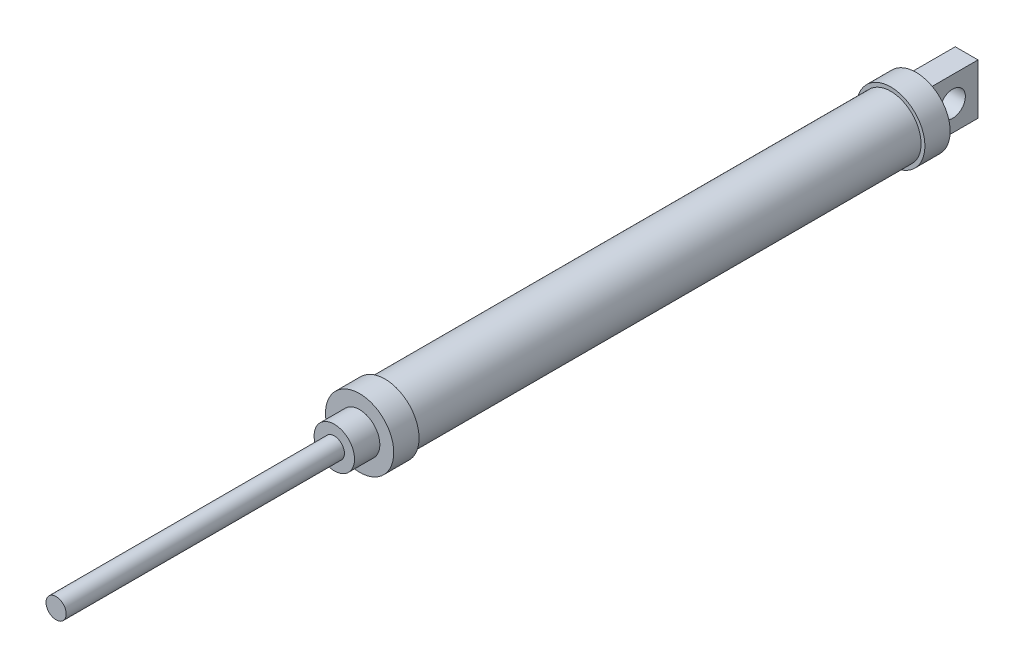
SolidWorks part; units mm, degrees
ref_plane "Front Plane" through (0, 0, 0) normal (0, 0, 1) x (1, 0, 0)
ref_plane "Top Plane" through (0, 0, 0) normal (0, 1, 0) x (1, 0, 0)
ref_plane "Right Plane" through (0, 0, 0) normal (1, 0, 0) x (0, 0, -1)
sketch "Sketch1" plane through (0, 0, 0) normal (0, 0, 1) x (1, 0, 0)
  circle A0 centre (0, 0) radius 13.5
  dimension "D1" = 27
extrude "Boss-Extrude1" add sketch "Sketch1" along normal blind 10
sketch "Sketch2" plane through (0, 0, 10) normal (0, 0, 1) x (1, 0, 0)
  circle A0 centre (0, 0) radius 8
  dimension "D1" = 16
extrude "Boss-Extrude2" add sketch "Sketch2" along normal blind 10
sketch "Sketch3" plane through (0, 0, 0) normal (0, 0, -1) x (-1, 0, 0)
  circle A0 centre (0, 0) radius 12
  dimension "D1" = 24
extrude "Boss-Extrude3" add sketch "Sketch3" along normal blind 200
sketch "Sketch4" plane through (0, 0, -200) normal (0, 0, -1) x (-1, 0, 0)
  circle A0 centre (0, 0) radius 13.5
  dimension "D1" = 27
extrude "Boss-Extrude4" add sketch "Sketch4" along normal blind 10 contours A0
sketch "Sketch5" plane through (0, 0, -210) normal (0, 0, -1) x (-1, 0, 0)
  line L1 (4.5, -10) -> (-4.5, -10)
  line L2 (4.5, -10) -> (4.5, 10)
  line L3 (4.5, 10) -> (-4.5, 10)
  line L4 (-4.5, -10) -> (-4.5, 10)
  line L5 (4.5, -10) -> (-4.5, 10) construction
  line L6 (4.5, 10) -> (-4.5, -10) construction
  point P0 (0, 0)
  dimension "D1" = 9
  dimension "D2" = 20
extrude "Boss-Extrude5" add sketch "Sketch5" along normal blind 20
sketch "Sketch6" plane through (4.5, 0, 0) normal (1, 0, 0) x (0, 0, -1)
  line L0 (210, 10) -> (230, -10) construction
  line L1 (230, -10) -> (210, -10) construction
  line L2 (230, -10) -> (230, 10) construction
  line L3 (230, 10) -> (210, -10) construction
  circle A0 centre (220, 0) radius 5
  dimension "D1" = 10
extrude "Cut-Extrude1" cut sketch "Sketch6" against normal blind 20 contours A0
sketch "Sketch8" plane through (0, 0, 20) normal (0, 0, 1) x (1, 0, 0)
  circle A0 centre (0, 0) radius 4
  dimension "D1" = 8
extrude "Boss-Extrude6" add sketch "Sketch8" along normal blind 110
